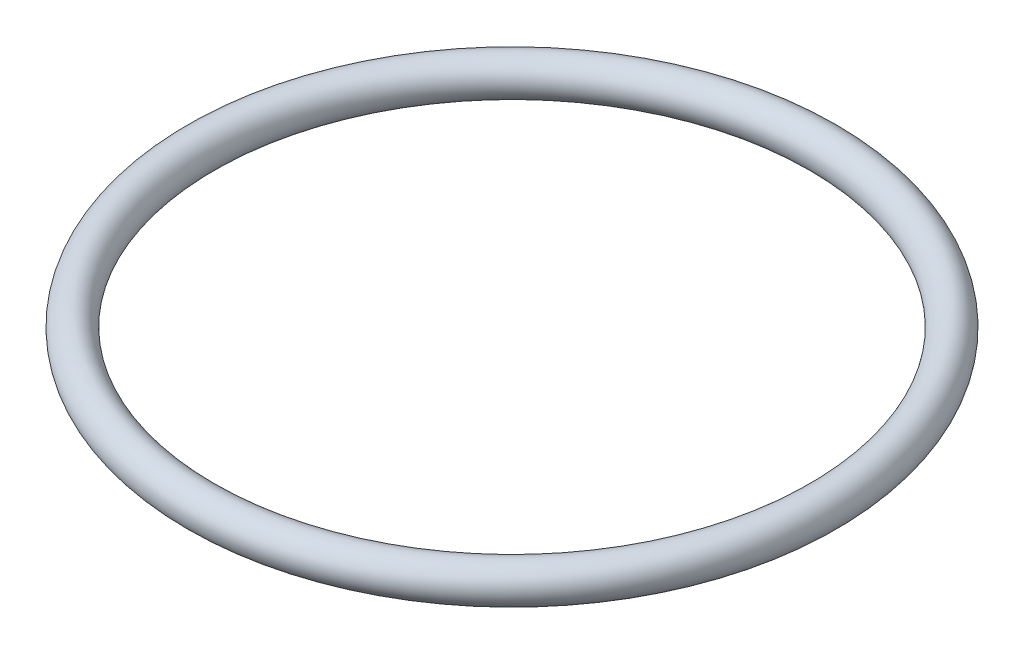
SolidWorks part; units mm, degrees
ref_plane "Płaszczyzna przednia" through (0, 0, 0) normal (0, 0, 1) x (1, 0, 0)
ref_plane "Płaszczyzna górna" through (0, 0, 0) normal (0, 1, 0) x (1, 0, 0)
ref_plane "Płaszczyzna prawa" through (0, 0, 0) normal (1, 0, 0) x (0, 0, -1)
sketch "Szkic1" plane through (0, 0, 0) normal (0, 0, 1) x (1, 0, 0)
  line L0 (0, 5.1245) -> (0, -7.9044) construction
  circle A0 centre (-25, -1.39) radius 1.5
  dimension "D1" = 3
  dimension "D2" = 25
revolve "Obrót1" add sketch "Szkic1" angle 360 about L0
